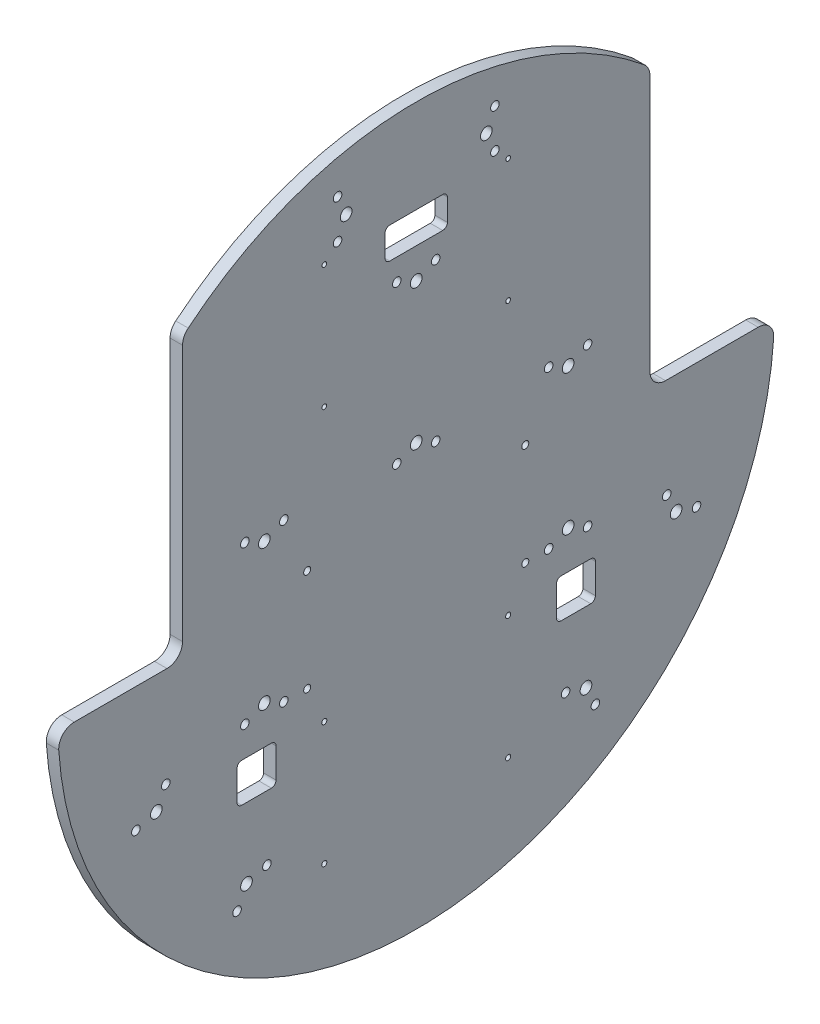
SolidWorks part; units mm, degrees
ref_plane "前视基准面" through (0, 0, 0) normal (0, 0, 1) x (1, 0, 0)
ref_plane "上视基准面" through (0, 0, 0) normal (0, 1, 0) x (1, 0, 0)
ref_plane "右视基准面" through (0, 0, 0) normal (1, 0, 0) x (0, 0, -1)
sketch "草图1" plane through (0, 0, 0) normal (1, 0, 0) x (0, 0, -1)
  circle A0 centre (0, 0) radius 230
  dimension "D1" = 460
extrude "凸台-拉伸1" add sketch "草图1" along normal blind 8
sketch "草图3" plane through (8, 0, 0) normal (1, 0, 0) x (0, 0, -1)
  line L0 (0, 0) -> (0, 50000) construction
  line L1 (150, 195) -> (230, 195)
  line L2 (150, 195) -> (150, -5)
  line L3 (150, -5) -> (230, -5)
  line L4 (230, 195) -> (230, -5)
  line L5 (-230, 195) -> (-230, -5)
  line L6 (-150, -5) -> (-230, -5)
  line L7 (-150, 195) -> (-150, -5)
  line L8 (-150, 195) -> (-230, 195)
  dimension "D1" = 80
  dimension "D2" = 200
  dimension "D3" = 5
  dimension "D4" = 150
extrude "切除-拉伸1" cut sketch "草图3" against normal blind 10
sketch "草图4" plane through (8, 0, 0) normal (1, 0, 0) x (0, 0, -1)
  line L0 (0, 0) -> (0, -50000) construction
  line L1 (0, 0) -> (38302.2222, -32139.3805) construction
  line L2 (166.8134, -81.2298) -> (108.9626, -150.1738) construction
  line L3 (-166.8134, -81.2298) -> (-108.9626, -150.1738) construction
  line L4 (0, 0) -> (-38302.2222, -32139.3805) construction
  line L5 (-50.5, 202.5) -> (50.5, 202.5) construction
  line L6 (-45, 190) -> (45, 190) construction
  line L7 (-50.5, 177.5) -> (50.5, 177.5) construction
  line L8 (115.0028, -162.4219) -> (179.9243, -85.0514) construction
  line L9 (-115.0028, -162.4219) -> (-179.9243, -85.0514) construction
  circle A0 centre (166.8134, -81.2298) radius 3.75
  circle A1 centre (108.9626, -150.1738) radius 3.75
  circle A2 centre (-108.9626, -150.1738) radius 3.75
  circle A3 centre (-166.8134, -81.2298) radius 3.75
  circle A4 centre (-45, 190) radius 3.75
  circle A5 centre (45, 190) radius 3.75
  circle A8 centre (-12.5, 35) radius 2.75
  circle A9 centre (12.5, 35) radius 2.75
  circle A10 centre (-50.5, 202.5) radius 2.75
  circle A11 centre (50.5, 202.5) radius 2.75
  circle A12 centre (-50.5, 177.5) radius 2.75
  circle A13 centre (50.5, 177.5) radius 2.75
  circle A14 centre (179.9243, -85.0514) radius 2.75
  circle A15 centre (115.0028, -162.4219) radius 2.75
  circle A16 centre (160.7732, -68.9817) radius 2.75
  circle A17 centre (95.8517, -146.3522) radius 2.75
  circle A18 centre (-160.7732, -68.9817) radius 2.75
  circle A19 centre (-179.9243, -85.0514) radius 2.75
  circle A20 centre (-95.8517, -146.3522) radius 2.75
  circle A21 centre (-115.0028, -162.4219) radius 2.75
  circle A22 centre (12.5, 136) radius 2.75
  circle A23 centre (-12.5, 136) radius 2.75
  circle A24 centre (0, 130.5) radius 3.75
  circle A25 centre (0, 40.5) radius 3.75
  dimension "D5" = 7.5
  dimension "D6" = 7.5
  dimension "D10" = 5.5
  dimension "D14" = 5.5
  dimension "D15" = 5.5
  dimension "D19" = 101
  dimension "D22" = 5.5
  dimension "D23" = 5.5
  dimension "D24" = 5.5
  dimension "D25" = 5.5
  dimension "D30" = 7.5
  dimension "D31" = 7.5
  dimension "D1" = 50
  dimension "D2" = 180
  dimension "D3" = 45
  dimension "D4" = 45
  dimension "D7" = 45
  dimension "D8" = 45
  dimension "D9" = 190
  dimension "D11" = 25
  dimension "D12" = 35
  dimension "D13" = 12.5
  dimension "D16" = 101
  dimension "D17" = 50.5
  dimension "D18" = 12.5
  dimension "D20" = 50.5
  dimension "D21" = 12.5
  dimension "D26" = 25
  dimension "D27" = 12.5
  dimension "D28" = 101
  dimension "D29" = 101
  dimension "D32" = 90
  dimension "D33" = 5.5
extrude "切除-拉伸2" cut sketch "草图4" against normal blind 10
sketch "草图6" plane through (8, 0, 0) normal (1, 0, 0) x (0, 0, -1)
  line L5 (-20, 170) -> (20, 170)
  line L6 (-20, 170) -> (-20, 150)
  line L7 (-20, 150) -> (20, 150)
  line L8 (20, 170) -> (20, 150)
  line L9 (-115, -80) -> (-90, -80)
  line L10 (-115, -80) -> (-115, -105)
  line L11 (-115, -105) -> (-90, -105)
  line L12 (-90, -80) -> (-90, -105)
  line L13 (90, -80) -> (115, -80)
  line L14 (90, -80) -> (90, -105)
  line L15 (90, -105) -> (115, -105)
  line L16 (115, -80) -> (115, -105)
  dimension "D1" = 25
  dimension "D2" = 80
  dimension "D3" = 90
  dimension "D4" = 80
  dimension "D5" = 20
  dimension "D6" = 40
  dimension "D7" = 20
  dimension "D8" = 150
  dimension "D9" = 90
extrude "切除-拉伸4" cut sketch "草图6" against normal blind 10
fillet "圆角2" radius 10 1 edges at (4, -5, 229.9456)
fillet "圆角3" radius 10 3 edges at (4, 174.356, 150) (4, 174.356, -150) (4, -5, -229.9456)
fillet "圆角4" radius 10 2 edges at (4, -5, -150) (4, -5, 150)
sketch "草图7" plane through (8, 0, 0) normal (1, 0, 0) x (0, 0, -1)
  line L0 (0, 0) -> (0, 50000) construction
  line L2 (85, 40) -> (110, 40) construction
  line L3 (85, 40) -> (85, -61) construction
  line L4 (85, -61) -> (110, -61) construction
  line L5 (110, 40) -> (110, -61) construction
  line L6 (-110, 40) -> (-110, -61) construction
  line L7 (-85, -61) -> (-110, -61) construction
  line L8 (-85, 40) -> (-85, -61) construction
  line L9 (-85, 40) -> (-110, 40) construction
  circle A32 centre (85, 40) radius 2.75
  circle A33 centre (110, 40) radius 2.75
  circle A34 centre (85, -61) radius 2.75
  circle A35 centre (110, -61) radius 2.75
  circle A36 centre (97.5, 34.5) radius 3.75
  circle A37 centre (97.5, -55.5) radius 3.75
  circle A38 centre (-97.5, -55.5) radius 3.75
  circle A39 centre (-97.5, 34.5) radius 3.75
  circle A40 centre (-110, -61) radius 2.75
  circle A41 centre (-85, -61) radius 2.75
  circle A42 centre (-110, 40) radius 2.75
  circle A43 centre (-85, 40) radius 2.75
  dimension "D4" = 40
  dimension "D8" = 90
  dimension "D9" = 5.5
  dimension "D2" = 101
  dimension "D5" = 5.5
  dimension "D10" = 25
  dimension "D6" = 7.5
  dimension "D7" = 7.5
  dimension "D1" = 25
  dimension "D3" = 85
extrude "切除-拉伸5" cut sketch "草图7" against normal blind 10
sketch "草图8" plane through (8, 0, 0) normal (1, 0, 0) x (0, 0, -1)
  line L1 (-59, 169) -> (59, 169) construction
  line L2 (-59, 169) -> (-59, 90) construction
  line L3 (-59, 90) -> (59, 90) construction
  line L4 (59, 169) -> (59, 90) construction
  circle A0 centre (-59, 169) radius 1.5
  circle A1 centre (-59, 90) radius 1.5
  circle A2 centre (59, 169) radius 1.5
  circle A3 centre (59, 90) radius 1.5
  dimension "D5" = 3
  dimension "D1" = 118
  dimension "D2" = 79
  dimension "D3" = 59
  dimension "D4" = 90
extrude "切除-拉伸6" cut sketch "草图8" against normal through all
sketch "草图9" plane through (8, 0, 0) normal (1, 0, 0) x (0, 0, -1)
  line L1 (-75, 20) -> (75, 20) construction
  line L2 (-75, 20) -> (-75, -77) construction
  line L3 (-75, -77) -> (75, -77) construction
  line L4 (75, 20) -> (75, -77) construction
  circle A1 centre (70, 4.25) radius 2.25
  circle A2 centre (70, -61.25) radius 2.25
  circle A3 centre (-70, 4.25) radius 2.25
  circle A4 centre (-70, -61.25) radius 2.25
  dimension "D5" = 65.5
  dimension "D6" = 4.5
  dimension "D8" = 15.75
  dimension "D9" = 65.5
  dimension "D1" = 97
  dimension "D2" = 150
  dimension "D3" = 75
  dimension "D4" = 20
  dimension "D7" = 10
  dimension "D10" = 140
extrude "切除-拉伸7" cut sketch "草图9" against normal blind 11
fillet "圆角5" radius 3 12 edges at (4, 170, -20) (4, 150, -20) (4, 150, 20) (4, 170, 20) (4, -80, -90) (4, -105, -90) (4, -105, -115) (4, -80, -115) (4, -80, 115) (4, -105, 115) (4, -105, 90) (4, -80, 90)
sketch "草图10" plane through (8, 0, 0) normal (1, 0, 0) x (0, 0, -1)
  line L1 (-59, -85) -> (59, -85) construction
  line L2 (-59, -85) -> (-59, -164) construction
  line L3 (-59, -164) -> (59, -164) construction
  line L4 (59, -85) -> (59, -164) construction
  circle A0 centre (-59, -85) radius 1.65
  circle A1 centre (59, -85) radius 1.65
  circle A2 centre (59, -164) radius 1.65
  circle A3 centre (-59, -164) radius 1.65
  dimension "D5" = 3.3
  dimension "D1" = 79
  dimension "D2" = 118
  dimension "D3" = 59
  dimension "D4" = 85
extrude "切除-拉伸8" cut sketch "草图10" against normal blind 10
